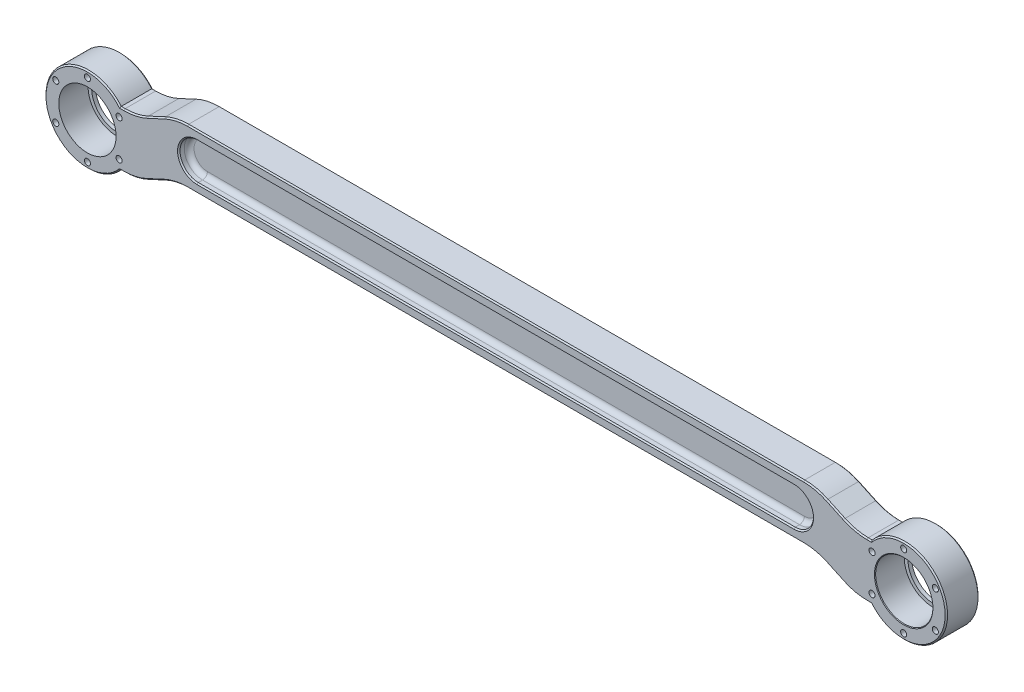
SolidWorks part; units mm, degrees
ref_plane "前视基准面" through (0, 0, 0) normal (0, 0, 1) x (1, 0, 0)
ref_plane "上视基准面" through (0, 0, 0) normal (0, 1, 0) x (1, 0, 0)
ref_plane "右视基准面" through (0, 0, 0) normal (1, 0, 0) x (0, 0, -1)
sketch "草图1" plane through (0, 0, 0) normal (0, 0, 1) x (1, 0, 0)
  line L0 (0, 22.5) -> (670, 22.5)
  line L1 (0, -22.5) -> (670, -22.5)
  arc A0 (0, 22.5) -> (0, -22.5) centre (0, 0) ccw
  arc A1 (670, -22.5) -> (670, 22.5) centre (670, 0) ccw
  dimension "D1" = 670
  dimension "D2" = 45
  dimension "D3" = 45
extrude "拉伸1" add sketch "草图1" along normal blind 27
sketch "草图2" plane through (0, 0, 27) normal (0, 0, 1) x (1, 0, 0)
  circle A0 centre (0, 0) radius 20.5
  circle A1 centre (670, 0) radius 20.5
  dimension "D1" = 41
  dimension "D2" = 41
extrude "切除-拉伸1" cut sketch "草图2" against normal blind 45
sketch "草图3" plane through (0, 0, 27) normal (0, 0, 1) x (1, 0, 0)
  line L0 (40, -22.5) -> (72.1676, -7.5)
  line L1 (0, -22.5) -> (670, -22.5) construction
  line L2 (72.1676, -7.5) -> (597.8324, -7.5)
  line L3 (597.8324, -7.5) -> (630, -22.5)
  line L4 (40, -22.5) -> (630, -22.5)
  arc A0 (0, 22.5) -> (0, -22.5) centre (0, 0) ccw construction
  circle A1 centre (670, 0) radius 20.5 construction
  dimension "D1" = 25
  dimension "D2" = 15
  dimension "D3" = 25
  dimension "D4" = 40
  dimension "D5" = 40
extrude "切除-拉伸2" cut sketch "草图3" against normal blind 50
sketch "草图4" plane through (0, 0, 27) normal (0, 0, 1) x (1, 0, 0)
  line L0 (670, 22.5) -> (0, 22.5) construction
  line L1 (0, -22.5) -> (40, -22.5) construction
  line L5 (630, 22.5) -> (40, 22.5)
  line L9 (40, 22.5) -> (72.1676, 37.5)
  line L10 (72.1676, 37.5) -> (597.8324, 37.5)
  line L11 (597.8324, 37.5) -> (630, 22.5)
  circle A0 centre (670, 0) radius 20.5 construction
  circle A1 centre (0, 0) radius 20.5 construction
  dimension "D1" = 15
  dimension "D2" = 25
  dimension "D3" = 25
  dimension "D4" = 45
  dimension "D5" = 40
  dimension "D6" = 40
extrude "拉伸2" add sketch "草图4" against normal blind 27
sketch "草图5" plane through (0, 0, 27) normal (0, 0, 1) x (1, 0, 0)
  line L1 (90, 30) -> (580, 30)
  line L2 (597.8324, 37.5) -> (72.1676, 37.5) construction
  line L3 (90, 0) -> (580, 0)
  arc A2 (580, 0) -> (580, 30) centre (580, 15) ccw
  arc A3 (90, 30) -> (90, 0) centre (90, 15) ccw
  circle A4 centre (670, 0) radius 20.5 construction
  circle A5 centre (0, 0) radius 20.5 construction
  dimension "D1" = 90
  dimension "D2" = 90
  dimension "D3" = 15
  dimension "D4" = 22.5
extrude "切除-拉伸3" cut sketch "草图5" against normal blind 8.5
sketch "草图7" plane through (0, 0, 0) normal (0, 0, -1) x (-1, 0, 0)
  line L0 (-90, 30) -> (-580, 30)
  line L1 (-90, 0) -> (-580, 0)
  arc A0 (-580, 30) -> (-580, 0) centre (-580, 15) ccw
  arc A1 (-90, 0) -> (-90, 30) centre (-90, 15) ccw
extrude "切除-拉伸4" cut sketch "草图7" against normal blind 8.5
chamfer "倒角2" distance 1 angle 45 8 edges at (595, 15, 0) (335, 0, 0) (75, 15, 0) (335, 30, 0) (335, 0, 27) (595, 15, 27) (335, 30, 27) (75, 15, 27)
fillet "圆角1" radius 4 8 edges at (595, 15, 18.5) (335, 0, 18.5) (75, 15, 18.5) (595, 15, 8.5) (335, 30, 8.5) (75, 15, 8.5) (335, 30, 18.5) (335, 0, 8.5)
fillet "圆角2" radius 45 8 edges at (597.8324, -7.5, 13.5) (630, -22.5, 13.5) (597.8324, 37.5, 13.5) (630, 22.5, 13.5) (40, 22.5, 13.5) (72.1676, -7.5, 13.5) (40, -22.5, 13.5) (72.1676, 37.5, 13.5)
sketch "草图8" plane through (0, 0, 27) normal (0, 0, 1) x (1, 0, 0)
  line L0 (0, 22.5) -> (26.8095, 22.5)
  line L1 (0, -22.5) -> (26.8095, -22.5)
  line L6 (670, 22.5) -> (643.1905, 22.5)
  line L7 (670, -22.5) -> (643.1905, -22.5)
  arc A0 (26.8095, 22.5) -> (26.8095, -22.5) centre (0, 0) ccw
  arc A1 (0, 22.5) -> (0, -22.5) centre (0, 0) ccw
  arc A2 (643.1905, -22.5) -> (643.1905, 22.5) centre (670, 0) ccw
  arc A3 (670, -22.5) -> (670, 22.5) centre (670, 0) ccw
  dimension "D1" = 35
  dimension "D2" = 70
extrude "拉伸3" add sketch "草图8" against normal blind 27
sketch "草图13" plane through (0, 0, 27) normal (0, 0, 1) x (1, 0, 0)
  circle A0 centre (0, 0) radius 23.5
  circle A1 centre (670, 0) radius 23.5
  dimension "D1" = 47
extrude "切除-拉伸8" cut sketch "草图13" against normal blind 24
sketch "草图14" plane through (0, 0, 27) normal (0, 0, 1) x (1, 0, 0)
  circle A0 centre (-25.9808, -15) radius 2.5
  circle A1 centre (644.0192, -15) radius 2.5
  circle A2 centre (670, -30) radius 2.5
  circle A3 centre (644.0192, 15) radius 2.5
  circle A4 centre (670, 30) radius 2.5
  circle A5 centre (-25.9808, 15) radius 2.5
  circle A6 centre (0, 30) radius 2.5
  circle A7 centre (0, -30) radius 2.5
  circle A8 centre (25.9808, 15) radius 2.5
  circle A9 centre (25.9808, -15) radius 2.5
  circle A10 centre (695.9808, 15) radius 2.5
  circle A11 centre (695.9808, -15) radius 2.5
extrude "切除-拉伸9" cut sketch "草图14" against normal blind 20
chamfer "倒角3" distance 0.5 angle 45 1 edges at (693.5, 0, 27)
chamfer "倒角4" distance 1 angle 45 40 edges at (705, 0, 27) (705, 0, 0) (641.5834, 22.5, 0) (630.2365, 23.5667, 0) (28.4166, 22.5, 0) (613.9162, 30, 0) (613.9162, 30, 27) (39.7635, 23.5667, 0) (597.5959, 36.4333, 0) (56.0838, 30, 0) (56.0838, 30, 27) (335, 37.5, 27) (335, 37.5, 0) (72.4041, 36.4333, 0) (-35, 0, 27) (-35, 0, 0) (641.5834, -22.5, 0) (630.2365, -21.4333, 0) (613.9162, -15, 0) (597.5959, -8.5667, 0) (335, -7.5, 0) (72.4041, -8.5667, 0) (56.0838, -15, 0) (28.4166, -22.5, 0) (39.7635, -21.4333, 0) (28.4166, 22.5, 27) (39.7635, 23.5667, 27) (72.4041, 36.4333, 27) (641.5834, 22.5, 27) (630.2365, 23.5667, 27) (597.5959, 36.4333, 27) (641.5834, -22.5, 27) (28.4166, -22.5, 27) (630.2365, -21.4333, 27) (39.7635, -21.4333, 27) (613.9162, -15, 27) (56.0838, -15, 27) (597.5959, -8.5667, 27) (72.4041, -8.5667, 27) (335, -7.5, 27)
sketch "草图15" plane through (0, -7.5, 0) normal (0, -1, 0) x (1, 0, 0)
  line L0 (-35, 26) -> (-35, 1) construction
  circle A0 centre (320, 13.5) radius 4
  circle A1 centre (360, 13.5) radius 4
  dimension "D2" = 355
extrude "切除-拉伸10" cut sketch "草图15" against normal blind 20
sketch "草图16" plane through (0, 0, 0) normal (0, 0, -1) x (-1, 0, 0)
  line L0 (-30.0237, 22.5) -> (-26.8095, 22.5) construction
  circle A3 centre (-54.9432, -2.5) radius 4
  circle A4 centre (-55, 17.4999) radius 4
  point P0 (-28.4166, 22.5)
  dimension "D1" = 55
  dimension "D2" = 55
  dimension "D3" = 20
  dimension "D4" = 8
  dimension "D5" = 8
  dimension "D6" = 25
extrude "切除-拉伸11" cut sketch "草图16" against normal blind 20
